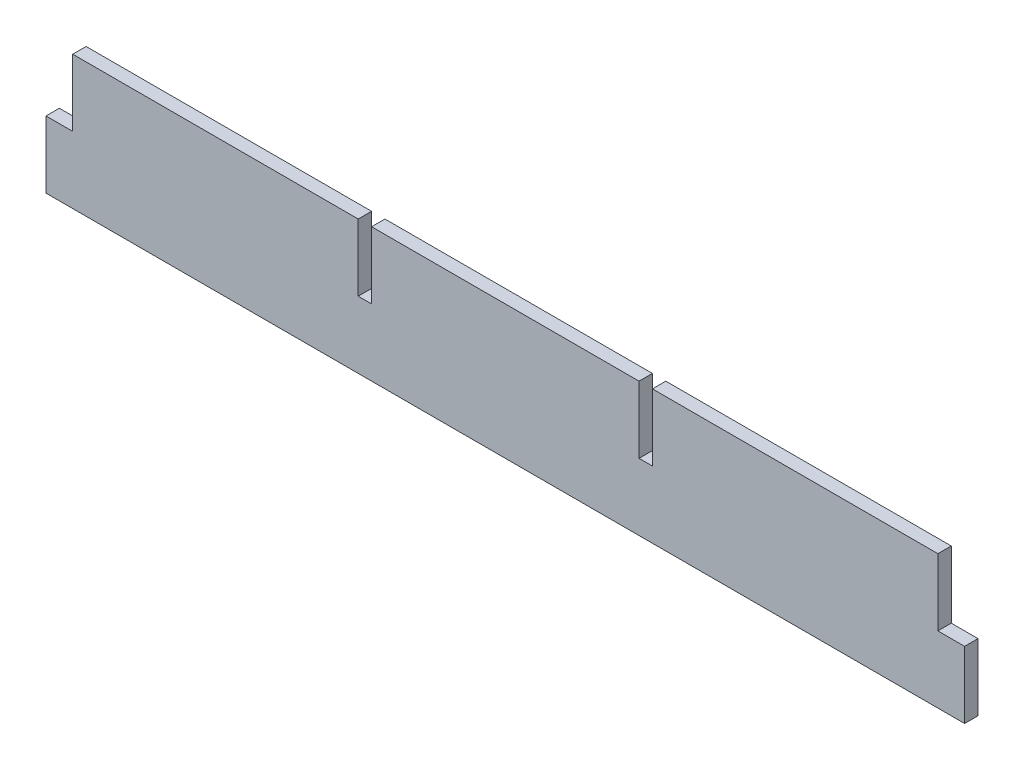
SolidWorks part; units mm, degrees
ref_plane "Front Plane" through (0, 0, 0) normal (0, 0, 1) x (1, 0, 0)
ref_plane "Top Plane" through (0, 0, 0) normal (0, 1, 0) x (1, 0, 0)
ref_plane "Right Plane" through (0, 0, 0) normal (1, 0, 0) x (0, 0, -1)
sketch "Sketch1" plane through (0, 0, 0) normal (0, 0, 1) x (1, 0, 0)
  line L0 (-323.475, 0) -> (-110, 0)
  line L1 (323.475, 0) -> (323.475, -50)
  line L2 (323.475, -50) -> (343.475, -50)
  line L3 (343.475, -50) -> (343.475, -100)
  line L4 (343.475, -100) -> (-343.475, -100)
  line L6 (-343.475, -50) -> (-343.475, -100)
  line L7 (-323.475, -50) -> (-343.475, -50)
  line L8 (-323.475, 0) -> (-323.475, -50)
  line L9 (0, 0) -> (0, -100) construction
  line L19 (-110, 0) -> (-110, -50)
  line L20 (-110, -50) -> (-100, -50)
  line L21 (-100, 0) -> (-100, -50)
  line L22 (110, -50) -> (100, -50)
  line L23 (110, 0) -> (110, -50)
  line L24 (100, 0) -> (100, -50)
  line L26 (110, 0) -> (323.475, 0)
  line L27 (-100, 0) -> (100, 0)
  dimension "D1" = 10
  dimension "D2" = 50
  dimension "D3" = 50
  dimension "D4" = 20
  dimension "D5" = 100
  dimension "D6" = 646.95
extrude "Boss-Extrude1" add sketch "Sketch1" along normal blind 10 contours L0 L9 L4 L3 L2 L1 L23 L22 L24 | L9 L0 L21 L20 L19 L8 L7 L6 L4
